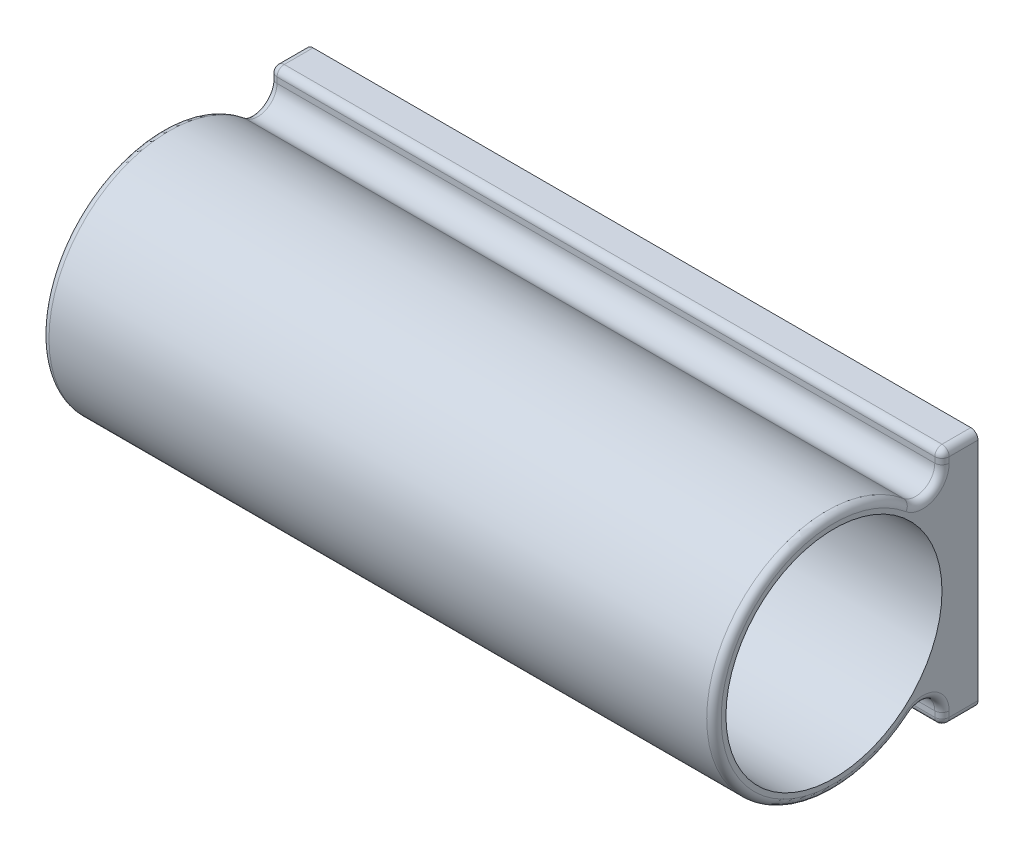
SolidWorks part; units mm, degrees
material "Латунь"
ref_plane "Спереди" through (0, 0, 0) normal (0, 0, 1) x (1, 0, 0)
ref_plane "Сверху" through (0, 0, 0) normal (0, 1, 0) x (1, 0, 0)
ref_plane "Справа" through (0, 0, 0) normal (1, 0, 0) x (0, 0, -1)
sketch "Эскиз1" plane through (0, 0, 0) normal (1, 0, 0) x (0, 0, -1)
  line L0 (0, 90.3755) -> (0, -85.5132) construction
  line L1 (-99.6773, 0) -> (73.2517, 0) construction
  line L2 (60, -50) -> (60, 50)
  line L3 (60, 50) -> (48, 50)
  line L4 (45, 47) -> (45, 44.6654)
  line L5 (60, -50) -> (48, -50)
  line L6 (45, -47) -> (45, -44.6654)
  arc A0 (31.8966, 38.5047) -> (31.8966, -38.5047) centre (0, 0) ccw
  arc A1 (31.8966, 38.5047) -> (45, 44.6654) centre (37, 44.6654) ccw
  arc A2 (31.8966, -38.5047) -> (45, -44.6654) centre (37, -44.6654) cw
  arc A3 (48, -50) -> (45, -47) centre (48, -47) cw
  arc A4 (48, 50) -> (45, 47) centre (48, 47) ccw
  point P14 (60, 0)
  point P20 (45, -50)
  point P23 (45, 50)
  dimension "D1" = 50
  dimension "D5" = 8
  dimension "D6" = 3
  dimension "D2" = 60
  dimension "D3" = 15
  dimension "D4" = 50
extrude "Бобышка-Вытянуть1" add sketch "Эскиз1" along normal mid plane 280
fillet "Скругление1" radius 3 18 edges at (-140, 50, -54) (-140, 49.1213, -45.8787) (-140, 45.8327, -45) (-140, 37.4257, -40.4039) (-140, -50, -54) (-140, -49.1213, -45.8787) (-140, -45.8327, -45) (-140, -37.4257, -40.4039) (-140, 0, 50) (140, -50, -54) (140, -49.1213, -45.8787) (140, -45.8327, -45) (140, -37.4257, -40.4039) (140, 0, 50) (140, 37.4257, -40.4039) (140, 45.8327, -45) (140, 49.1213, -45.8787) (140, 50, -54)
sketch "Эскиз2" plane through (0, 0, 0) normal (1, 0, 0) x (0, 0, -1)
  line L0 (-60.4034, 0) -> (100.5471, 0) construction
  line L1 (60, 0) -> (60, 10)
  line L2 (60, -47) -> (60, 47) construction
  line L3 (60, 10) -> (80, 10)
  line L4 (80, 10) -> (80, 20)
  line L5 (60, 0) -> (90, 0)
  line L6 (90, 0) -> (90, -13.6134) construction
  arc A0 (80, 20) -> (90, 0) centre (65, 0) cw
  dimension "D3" = 30
  dimension "D1" = 10
  dimension "D2" = 20
  dimension "D4" = 20
revolve "Повернуть1" add sketch "Эскиз2" angle 360 about L0
sketch "Эскиз3" plane through (140, 0, 0) normal (1, 0, 0) x (0, 0, -1)
  line L0 (-60.3282, 0) -> (106.0125, 0) construction
  circle A0 centre (0, 0) radius 45
  dimension "D1" = 90
extrude "Вырез-Вытянуть1" cut sketch "Эскиз3" against normal offset from surface (275 mm away) 5 up to face at (-140, 0, -37.5451)
sketch "Эскиз4" plane through (0, 0, -60) normal (0, 0, -1) x (-1, 0, 0)
  line L0 (0, 70.1064) -> (0, -71.702) construction
  line L1 (-151.4817, 0) -> (163.6481, 0) construction
  circle A0 centre (120, 0) radius 10
  dimension "D1" = 20
  dimension "D2" = 120
extrude "Вырез-Вытянуть2" cut sketch "Эскиз4" against normal blind 30
